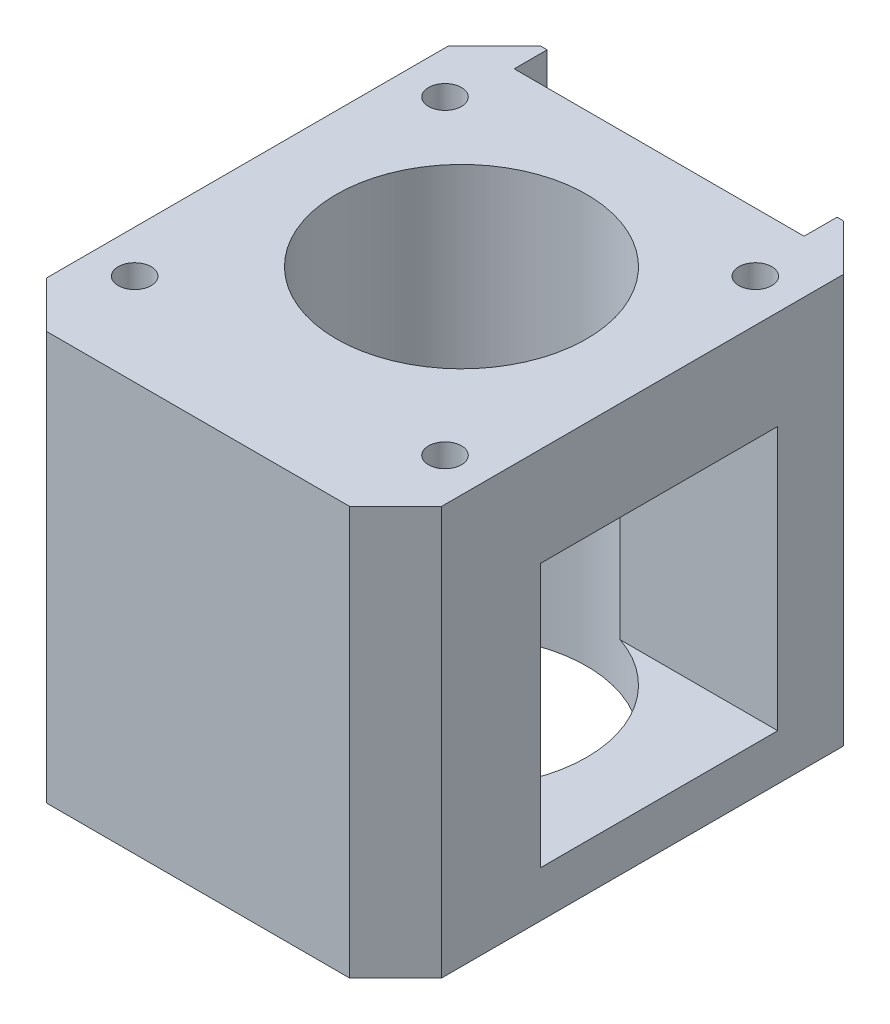
SolidWorks part; units mm, degrees
ref_plane "Front Plane" through (0, 0, 0) normal (0, 0, 1) x (1, 0, 0)
ref_plane "Top Plane" through (0, 0, 0) normal (0, 1, 0) x (1, 0, 0)
ref_plane "Right Plane" through (0, 0, 0) normal (1, 0, 0) x (0, 0, -1)
sketch "Sketch1" plane through (0, 0, 0) normal (0, 1, 0) x (1, 0, 0)
  line L1 (-30, 37.5) -> (30, 37.5)
  line L2 (-30, 37.5) -> (-30, -37.5)
  line L3 (-30, -37.5) -> (30, -37.5)
  line L4 (30, 37.5) -> (30, -37.5)
  line L5 (-30, 37.5) -> (30, -37.5) construction
  line L6 (-30, -37.5) -> (30, 37.5) construction
  point P0 (0, 0)
  dimension "D1" = 60
  dimension "D2" = 75
extrude "Boss-Extrude1" add sketch "Sketch1" along normal blind 62
sketch "Sketch2" plane through (0, 62, 0) normal (0, 1, 0) x (1, 0, 0)
  line L0 (30, 37.5) -> (-30, 37.5) construction
  line L1 (-22, 37.5) -> (22, 37.5)
  line L2 (-22, 37.5) -> (-22, 32.5)
  line L3 (-22, 32.5) -> (22, 32.5)
  line L4 (22, 37.5) -> (22, 32.5)
  line L5 (30, -37.5) -> (30, 37.5) construction
  circle A0 centre (0, 2.5) radius 19
  dimension "D5" = 38
  dimension "D1" = 5
  dimension "D2" = 44
  dimension "D3" = 8
  dimension "D4" = 30
extrude "Cut-Extrude1" cut sketch "Sketch2" against normal up to surface (62 mm away) up to face at (0, 0, 0)
sketch "Sketch3" plane through (30, 0, 0) normal (1, 0, 0) x (0, 0, -1)
  line L0 (-37.5, 62) -> (37.5, 62) construction
  line L1 (-15.5, 47) -> (20.5, 47)
  line L2 (-15.5, 47) -> (-15.5, 7)
  line L3 (-15.5, 7) -> (20.5, 7)
  line L4 (20.5, 47) -> (20.5, 7)
  line L5 (37.5, 62) -> (37.5, 0) construction
  dimension "D1" = 36
  dimension "D2" = 40
  dimension "D3" = 15
  dimension "D4" = 17
extrude "Cut-Extrude2" cut sketch "Sketch3" against normal up to surface (23.9172 mm away)
chamfer "Chamfer1" distance 7 angle 45 4 edges at (-30, 31, 37.5) (-30, 31, -37.5) (30, 31, -37.5) (30, 31, 37.5)
sketch "Sketch4" plane through (0, 0, -32.5) normal (0, 0, -1) x (-1, 0, 0)
  line L0 (-22, 0) -> (-22, 62) construction
  line L1 (22, 62) -> (-22, 62) construction
  circle A0 centre (-14, 53) radius 2.5
  circle A1 centre (14, 53) radius 2.5
  circle A2 centre (-14, 9) radius 2.5
  circle A3 centre (14, 9) radius 2.5
  dimension "D1" = 5
  dimension "D2" = 8
  dimension "D3" = 9
  dimension "D6" = 44
  dimension "D4" = 2
  dimension "D5" = 2
extrude "Cut-Extrude3" cut sketch "Sketch4" against normal blind 10
sketch "Sketch5" plane through (0, 62, 0) normal (0, 1, 0) x (1, 0, 0)
  circle A0 centre (-23.55, 23.55) radius 2.5
  circle A1 centre (23.55, 23.55) radius 2.5
  circle A2 centre (23.55, -23.55) radius 2.5
  circle A3 centre (-23.55, -23.55) radius 2.5
  point P12 (0, 0)
  dimension "D1" = 5
  dimension "D2" = 23.55
  dimension "D3" = 23.55
  dimension "D5" = 47.1
  dimension "D4" = 4
extrude "Cut-Extrude4" cut sketch "Sketch5" against normal blind 20
